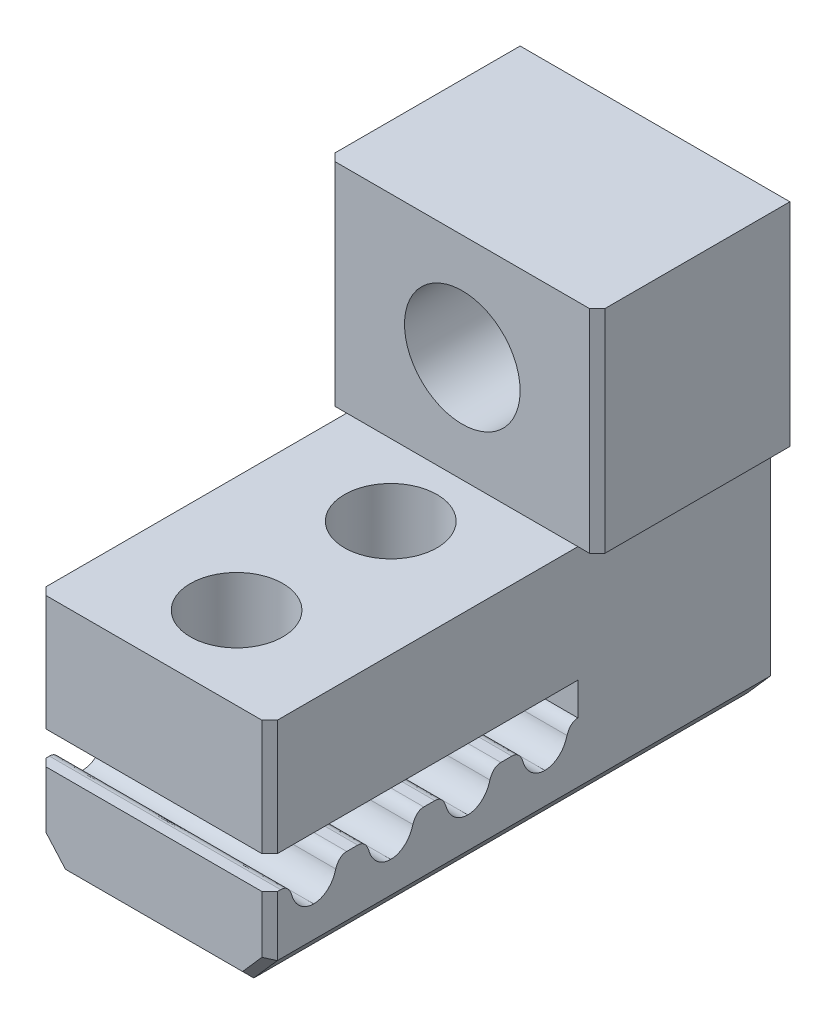
SolidWorks part; units mm, degrees
ref_plane "Front Plane" through (0, 0, 0) normal (0, 0, 1) x (1, 0, 0)
ref_plane "Top Plane" through (0, 0, 0) normal (0, 1, 0) x (1, 0, 0)
ref_plane "Right Plane" through (0, 0, 0) normal (1, 0, 0) x (0, 0, -1)
sketch "Sketch1" plane through (0, 0, 0) normal (0, 0, 1) x (1, 0, 0)
  line L0 (3, 3.05) -> (3, -2.2538)
  line L1 (-3, 3.05) -> (-3, -2.2538)
  line L7 (-3, 3.05) -> (3, 3.05)
  line L13 (-3, -2.2538) -> (-2.3882, -2.95)
  line L14 (3, -2.2538) -> (2.3882, -2.95)
  line L16 (-2.3882, -2.95) -> (2.3882, -2.95)
extrude "Boss-Extrude1" add sketch "Sketch1" along normal blind 13
sketch "Sketch6" plane through (0, 3.05, 0) normal (0, 1, 0) x (1, 0, 0)
  line L1 (-3, 0) -> (3, 0)
  line L2 (-3, 0) -> (-3, -5)
  line L3 (-3, -5) -> (3, -5)
  line L4 (3, 0) -> (3, -5)
  line L7 (3, 0) -> (-3, 0) construction
  line L9 (3, -13) -> (3, 0) construction
  line L10 (-3, -13) -> (-3, 0) construction
extrude "Boss-Extrude4" add sketch "Sketch6" along normal blind 5.6
sketch "Sketch16" plane through (0, 3.05, 0) normal (0, 1, 0) x (1, 0, 0)
  line L4 (3, -5) -> (-3, -5)
  line L5 (-3, -5) -> (-3, -13)
  line L6 (-3, -13) -> (3, -13)
  line L7 (3, -13) -> (3, -5)
  line L8 (3, -5) -> (-3, -5)
  line L9 (-3, -5) -> (-3, -13)
  line L10 (-3, -13) -> (3, -13)
  line L11 (3, -13) -> (3, -5)
  dimension "D1" = 0
extrude "Boss-Extrude5" add sketch "Sketch16" along normal blind 0.1
sketch "Sketch18" plane through (0, 0, 0) normal (1, 0, 0) x (0, 0, -1)
  line L0 (-8.8572, -0.0702) -> (-12.8572, -0.0702)
  line L2 (-12.8572, -0.7) -> (-12.7144, -0.7)
  line L3 (-11, -0.7) -> (-10.8572, -0.7)
  line L4 (-10.8572, -0.7) -> (-10.7144, -0.7)
  line L5 (-9, -0.7) -> (-8.8572, -0.7)
  line L6 (-8.8572, -0.7) -> (-8.7144, -0.7)
  line L7 (-7, -0.7) -> (-6.8572, -0.7)
  line L8 (-6.8572, -0.7) -> (-6.7144, -0.7)
  line L9 (-5, -0.0702) -> (-5, -0.7)
  line L11 (-5, -0.0702) -> (-8.8572, -0.0702)
  line L12 (-13, -2.95) -> (0, -2.95) construction
  line L13 (-5.8572, -1.45) -> (-5, -1.45) construction
  line L14 (-5, -1.45) -> (-11.8572, -1.45) construction
  line L15 (-5, 3.15) -> (-5, -1.45) construction
  line L16 (-5, -0.7) -> (-5, -1.45) construction
  line L17 (-12.8572, -0.0702) -> (-13, -0.0702)
  line L20 (-13, -0.0702) -> (-13, -0.7)
  line L22 (-12.8572, -0.7) -> (-13, -0.7)
  spline S0 degree 2 poles (-12.7144, -0.7) (-12.5198, -0.7) (-12.43, -0.9509) knots 0.103448 0.103448 0.103448 0.137931 0.137931 0.137931
  spline S1 degree 3 poles (-12.43, -0.9509) (-12.3594, -1.2388) (-12.13, -1.45) (-11.8572, -1.45) knots 0.137931 0.137931 0.137931 0.137931 0.172414 0.172414 0.172414 0.172414
  spline S2 degree 3 poles (-11.8572, -1.45) (-11.5844, -1.45) (-11.355, -1.2388) (-11.2844, -0.9509) knots 0.172414 0.172414 0.172414 0.172414 0.206897 0.206897 0.206897 0.206897
  spline S3 degree 2 poles (-11.2844, -0.9509) (-11.1946, -0.7) (-11, -0.7) knots 0.206897 0.206897 0.206897 0.241379 0.241379 0.241379
  spline S4 degree 2 poles (-10.7144, -0.7) (-10.5198, -0.7) (-10.43, -0.9509) knots 0.310345 0.310345 0.310345 0.344828 0.344828 0.344828
  spline S5 degree 3 poles (-10.43, -0.9509) (-10.3594, -1.2388) (-10.13, -1.45) (-9.8572, -1.45) knots 0.344828 0.344828 0.344828 0.344828 0.37931 0.37931 0.37931 0.37931
  spline S6 degree 3 poles (-9.8572, -1.45) (-9.5844, -1.45) (-9.355, -1.2388) (-9.2844, -0.9509) knots 0.37931 0.37931 0.37931 0.37931 0.413793 0.413793 0.413793 0.413793
  spline S7 degree 2 poles (-9.2844, -0.9509) (-9.1946, -0.7) (-9, -0.7) knots 0.413793 0.413793 0.413793 0.448276 0.448276 0.448276
  spline S8 degree 2 poles (-8.7144, -0.7) (-8.5198, -0.7) (-8.43, -0.9509) knots 0.517241 0.517241 0.517241 0.551724 0.551724 0.551724
  spline S9 degree 3 poles (-8.43, -0.9509) (-8.3594, -1.2388) (-8.13, -1.45) (-7.8572, -1.45) knots 0.551724 0.551724 0.551724 0.551724 0.586207 0.586207 0.586207 0.586207
  spline S10 degree 3 poles (-7.8572, -1.45) (-7.5844, -1.45) (-7.355, -1.2388) (-7.2844, -0.9509) knots 0.586207 0.586207 0.586207 0.586207 0.62069 0.62069 0.62069 0.62069
  spline S11 degree 2 poles (-7.2844, -0.9509) (-7.1946, -0.7) (-7, -0.7) knots 0.62069 0.62069 0.62069 0.655172 0.655172 0.655172
  spline S12 degree 2 poles (-6.7144, -0.7) (-6.5198, -0.7) (-6.43, -0.9509) knots 0.724138 0.724138 0.724138 0.758621 0.758621 0.758621
  spline S13 degree 3 poles (-6.43, -0.9509) (-6.3594, -1.2388) (-6.13, -1.45) (-5.8572, -1.45) knots 0.758621 0.758621 0.758621 0.758621 0.793103 0.793103 0.793103 0.793103
  spline S14 degree 3 poles (-5.8572, -1.45) (-5.5844, -1.45) (-5.355, -1.2388) (-5.2844, -0.9509) knots 0.793103 0.793103 0.793103 0.793103 0.827586 0.827586 0.827586 0.827586
  spline S15 degree 2 poles (-5.2844, -0.9509) (-5.1946, -0.7) (-5, -0.7) knots 0.827586 0.827586 0.827586 0.862069 0.862069 0.862069
  dimension "D1" = 1.5
  dimension "D2" = 1.3798
extrude "Cut-Extrude6" cut sketch "Sketch18" against normal blind 3.6 and the other way blind 4
sketch "Sketch15" plane through (0, 8.65, 0) normal (0, 1, 0) x (1, 0, 0)
  line L0 (0, -13) -> (0, -5) construction
  line L1 (-3, -13) -> (3, -13) construction
  line L2 (-3, -5) -> (3, -5) construction
  line L3 (2.008, -10.7144) -> (2.008, -11) construction
  line L4 (3, -10.7144) -> (-3, -10.7144) construction
  line L5 (3, -11) -> (-3, -11) construction
  line L6 (2.008, -10.8572) -> (0, -10.8572) construction
  line L7 (1.0382, -6.7144) -> (1.0382, -7) construction
  line L8 (3, -6.7144) -> (-3, -6.7144) construction
  line L9 (3, -7) -> (-3, -7) construction
  line L10 (1.0382, -6.8572) -> (0, -6.8572) construction
  circle A0 centre (0, -6.8572) radius 1.5 construction
  circle A1 centre (0, -10.8572) radius 1.5 construction
  circle A2 centre (0, -10.8572) radius 1.2
  circle A4 centre (0, -6.8572) radius 1.2
extrude "Cut-Extrude7" cut sketch "Sketch15" against normal up to surface (8.7202 mm away) up to face at (0, -0.0702, 9)
sketch "Sketch19" plane through (0, -0.0702, 0) normal (0, -1, 0) x (1, 0, 0)
  line L4 (-3, 13) -> (-3, 5)
  line L5 (-3, 5) -> (3, 5)
  line L6 (3, 5) -> (3, 13)
  line L7 (3, 13) -> (-3, 13)
  line L8 (-3, 13) -> (-3, 5)
  line L9 (-3, 5) -> (3, 5)
  line L10 (3, 5) -> (3, 13)
  line L11 (3, 13) -> (-3, 13)
  circle A0 centre (0, 10.8572) radius 1.2 construction
  circle A1 centre (0, 6.8572) radius 1.2 construction
  circle A2 centre (0, 10.8572) radius 1.2
  circle A3 centre (0, 6.8572) radius 1.2
  dimension "D1" = 0
extrude "Cut-Extrude8" cut sketch "Sketch19" against normal blind 0.2202
sketch "Sketch12" plane through (0, 0, 5) normal (0, 0, 1) x (1, 0, 0)
  line L0 (-3, 5.9) -> (0, 5.9) construction
  line L1 (-3, 8.65) -> (-3, 3.15) construction
  line L2 (0, 5.9) -> (0, 8.65) construction
  line L3 (-3, 8.65) -> (3, 8.65) construction
  circle A0 centre (0, 5.9) radius 1.5 construction
  circle A1 centre (0, 5.9) radius 1.5
extrude "Cut-Extrude5" cut sketch "Sketch12" against normal blind 6
chamfer "Chamfer1" distance 0.2 angle 45 7 edges at (-3, 1.65, 13) (3, 1.65, 13) (3, -1.4769, 13) (2.6941, -2.6019, 13) (-3, -1.4769, 13) (-2.6941, -2.6019, 13) (0, -2.95, 13)
sketch "Sketch20" plane through (3, 0, 0) normal (1, 0, 0) x (0, 0, -1)
  line L1 (-5, 3.15) -> (0, 3.15)
  line L2 (-5, 3.15) -> (-5, 8.65)
  line L3 (-5, 8.65) -> (0, 8.65)
  line L4 (0, 3.15) -> (0, 8.65)
extrude "Boss-Extrude6" add sketch "Sketch20" along normal blind 0.5
sketch "Sketch21" plane through (-3, 0, 0) normal (-1, 0, 0) x (0, 0, 1)
  line L1 (5, 3.15) -> (0, 3.15)
  line L2 (5, 3.15) -> (5, 8.65)
  line L3 (5, 8.65) -> (0, 8.65)
  line L4 (0, 3.15) -> (0, 8.65)
extrude "Boss-Extrude7" add sketch "Sketch21" along normal blind 0.5
chamfer "Chamfer2" distance 0.2 angle 45 2 edges at (-3.5, 5.9, 5) (3.5, 5.9, 5)
